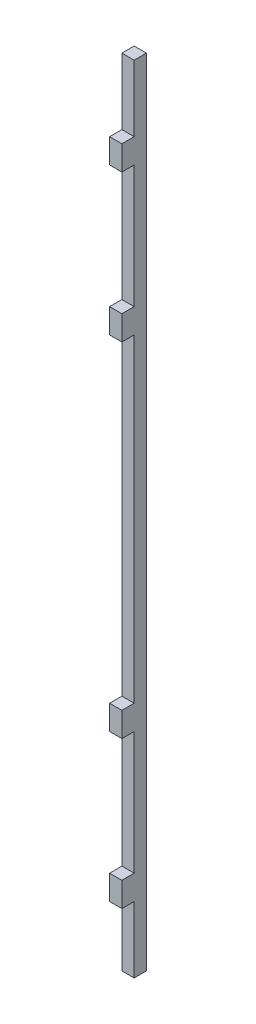
SolidWorks part; units mm, degrees
ref_plane "Front Plane" through (0, 0, 0) normal (1, 0, 0) x (0, 1, 0)
ref_plane "Top Plane" through (0, 0, 0) normal (0, 0, 1) x (0, 1, 0)
ref_plane "Right Plane" through (0, 0, 0) normal (0, 1, 0) x (-1, 0, 0)
sketch "Sketch1" plane through (0, 0, 0) normal (1, 0, 0) x (0, 1, 0)
  line L0 (0, 0) -> (70, 0) construction
  line L1 (70, 0) -> (130, 0) construction
  line L2 (70, 0) -> (70, 2.5) construction
  line L3 (130, 0) -> (130, 2.5) construction
  line L4 (130, 0) -> (162, 0) construction
  line L5 (65, 0) -> (75, 0)
  line L6 (65, 0) -> (65, 5)
  line L7 (65, 5) -> (75, 5)
  line L8 (75, 0) -> (75, 5)
  line L9 (65, 0) -> (75, 5) construction
  line L10 (65, 5) -> (75, 0) construction
  line L11 (125, 0) -> (135, 0)
  line L12 (125, 0) -> (125, 5)
  line L13 (125, 5) -> (135, 5)
  line L14 (135, 0) -> (135, 5)
  line L15 (125, 0) -> (135, 5) construction
  line L16 (125, 5) -> (135, 0) construction
  line L17 (0, 0) -> (162, 0)
  line L18 (0, 0) -> (0, -5)
  line L19 (0, -5) -> (162, -5)
  line L20 (162, -5) -> (162, 0)
  point P4 (0, 0)
  dimension "D1" = 70
  dimension "D2" = 60
  dimension "D3" = 2.5
  dimension "D4" = 2.5
  dimension "D5" = 10
  dimension "D6" = 5
  dimension "D7" = 162
  dimension "D8" = 5
extrude "Boss-Extrude1" add sketch "Sketch1" along normal mid plane 5 contours L19 L20 L17 L11 L5 L18 | L5 L8 L7 L6 | L11 L14 L13 L12
mirror "Mirror1" about plane through (0, 0, 0) normal (0, 1, 0) of "Boss-Extrude1"
